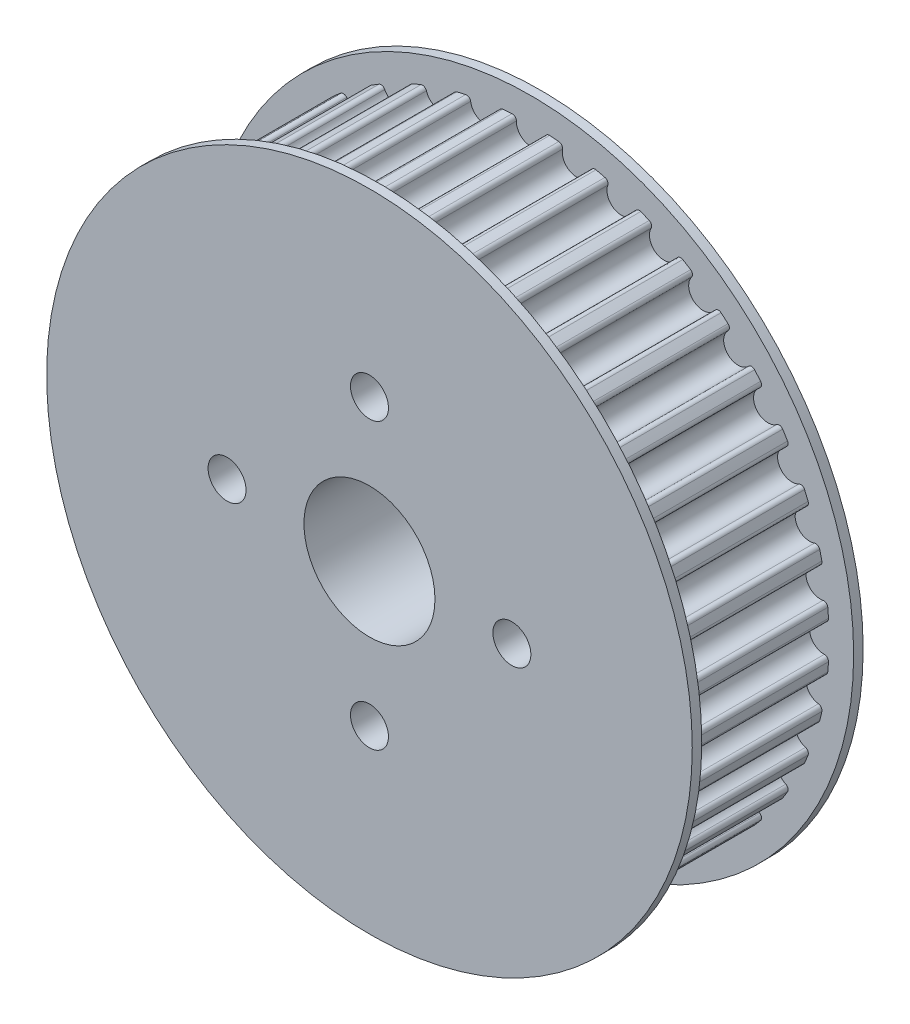
SolidWorks part; units mm, degrees
ref_plane "Front Plane" through (0, 0, 0) normal (0, 0, 1) x (1, 0, 0)
ref_plane "Top Plane" through (0, 0, 0) normal (0, 1, 0) x (1, 0, 0)
ref_plane "Right Plane" through (0, 0, 0) normal (1, 0, 0) x (0, 0, -1)
sketch "Sketch1" plane through (0, 0, 0) normal (0, 0, 1) x (1, 0, 0)
  line L0 (0, 0) -> (0, 52.0511) construction
  line L1 (0, 0) -> (78.6588, 0) construction
  line L2 (0, 0) -> (7.0914, 44.7731) construction
  arc A2 (0, 29.35) -> (1.5246, 30.9088) centre (0, 30.875) ccw
  arc A3 (1.9816, 31.3474) -> (1.5246, 30.9088) centre (1.9545, 30.9183) ccw
  arc A4 (3.3293, 30.7667) -> (4.5914, 28.9887) centre (4.8299, 30.4949) ccw
  arc A5 (3.3293, 30.7667) -> (2.9466, 31.2715) centre (2.9062, 30.8434) ccw
  arc A6 (2.9466, 31.2715) -> (1.9816, 31.3474) centre (0, 0) ccw
  arc A7 (4.5914, 28.9887) -> (6.3411, 30.2897) centre (4.8299, 30.4949) ccw
  arc A8 (6.8611, 30.6515) -> (6.3411, 30.2897) centre (6.7671, 30.2319) ccw
  arc A9 (7.8022, 30.4255) -> (6.8611, 30.6515) centre (0, 0) ccw
  arc A10 (8.1013, 29.8671) -> (7.8022, 30.4255) centre (7.6954, 30.009) ccw
  arc A11 (8.1013, 29.8671) -> (9.0696, 27.9135) centre (9.5409, 29.3639) ccw
  arc A12 (9.0696, 27.9135) -> (11.0013, 28.9248) centre (9.5409, 29.3639) ccw
  arc A13 (11.5715, 29.2008) -> (11.0013, 28.9248) centre (11.4131, 28.8011) ccw
  arc A14 (12.4658, 28.8304) -> (11.5715, 29.2008) centre (0, 0) ccw
  arc A15 (12.6738, 28.2321) -> (12.4658, 28.8304) centre (12.2951, 28.4357) ccw
  arc A16 (12.6738, 28.2321) -> (13.3246, 26.151) centre (14.017, 27.5098) ccw
  arc A17 (13.3246, 26.151) -> (15.3907, 26.8477) centre (14.017, 27.5098) ccw
  arc A18 (15.9971, 27.0311) -> (15.3907, 26.8477) centre (15.7781, 26.6611) ccw
  arc A19 (16.8224, 26.5254) -> (15.9971, 27.0311) centre (0, 0) ccw
  arc A20 (16.9343, 25.9019) -> (16.8224, 26.5254) centre (16.5921, 26.1623) ccw
  arc A21 (16.9343, 25.9019) -> (17.2515, 23.7446) centre (18.1479, 24.9784) ccw
  arc A22 (17.2515, 23.7446) -> (19.4012, 24.1096) centre (18.1479, 24.9784) ccw
  arc A23 (20.0287, 24.1958) -> (19.4012, 24.1096) centre (19.7546, 23.8646) ccw
  arc A24 (20.7647, 23.5672) -> (20.0287, 24.1958) centre (0, 0) ccw
  arc A25 (20.7777, 22.9339) -> (20.7647, 23.5672) centre (20.4805, 23.2446) ccw
  arc A26 (20.7777, 22.9339) -> (20.7536, 20.7536) centre (21.8319, 21.8319) ccw
  arc A27 (20.7536, 20.7536) -> (22.9339, 20.7777) centre (21.8319, 21.8319) ccw
  arc A28 (23.5672, 20.7647) -> (22.9339, 20.7777) centre (23.2446, 20.4805) ccw
  arc A29 (24.1958, 20.0287) -> (23.5672, 20.7647) centre (0, 0) ccw
  arc A30 (24.1096, 19.4012) -> (24.1958, 20.0287) centre (23.8646, 19.7546) ccw
  arc A31 (24.1096, 19.4012) -> (23.7446, 17.2515) centre (24.9784, 18.1479) ccw
  arc A32 (23.7446, 17.2515) -> (25.9019, 16.9343) centre (24.9784, 18.1479) ccw
  arc A33 (26.5254, 16.8224) -> (25.9019, 16.9343) centre (26.1623, 16.5921) ccw
  arc A34 (27.0311, 15.9971) -> (26.5254, 16.8224) centre (0, 0) ccw
  arc A35 (26.8477, 15.3907) -> (27.0311, 15.9971) centre (26.6611, 15.7781) ccw
  arc A36 (26.8477, 15.3907) -> (26.151, 13.3246) centre (27.5098, 14.017) ccw
  arc A37 (26.151, 13.3246) -> (28.2321, 12.6738) centre (27.5098, 14.017) ccw
  arc A38 (28.8304, 12.4658) -> (28.2321, 12.6738) centre (28.4357, 12.2951) ccw
  arc A39 (29.2008, 11.5715) -> (28.8304, 12.4658) centre (0, 0) ccw
  arc A40 (28.9248, 11.0013) -> (29.2008, 11.5715) centre (28.8011, 11.4131) ccw
  arc A41 (28.9248, 11.0013) -> (27.9135, 9.0696) centre (29.3639, 9.5409) ccw
  arc A42 (27.9135, 9.0696) -> (29.8671, 8.1013) centre (29.3639, 9.5409) ccw
  arc A43 (30.4255, 7.8022) -> (29.8671, 8.1013) centre (30.009, 7.6954) ccw
  arc A44 (30.6515, 6.8611) -> (30.4255, 7.8022) centre (0, 0) ccw
  arc A45 (30.2897, 6.3411) -> (30.6515, 6.8611) centre (30.2319, 6.7671) ccw
  arc A46 (30.2897, 6.3411) -> (28.9887, 4.5914) centre (30.4949, 4.8299) ccw
  arc A47 (28.9887, 4.5914) -> (30.7667, 3.3293) centre (30.4949, 4.8299) ccw
  arc A48 (31.2715, 2.9466) -> (30.7667, 3.3293) centre (30.8434, 2.9062) ccw
  arc A49 (31.3474, 1.9816) -> (31.2715, 2.9466) centre (0, 0) ccw
  arc A50 (30.9088, 1.5246) -> (31.3474, 1.9816) centre (30.9183, 1.9545) ccw
  arc A51 (30.9088, 1.5246) -> (29.35, 0) centre (30.875, 0) ccw
  arc A52 (29.35, 0) -> (30.9088, -1.5246) centre (30.875, 0) ccw
  arc A53 (31.3474, -1.9816) -> (30.9088, -1.5246) centre (30.9183, -1.9545) ccw
  arc A54 (31.2715, -2.9466) -> (31.3474, -1.9816) centre (0, 0) ccw
  arc A55 (30.7667, -3.3293) -> (31.2715, -2.9466) centre (30.8434, -2.9062) ccw
  arc A56 (30.7667, -3.3293) -> (28.9887, -4.5914) centre (30.4949, -4.8299) ccw
  arc A57 (28.9887, -4.5914) -> (30.2897, -6.3411) centre (30.4949, -4.8299) ccw
  arc A58 (30.6515, -6.8611) -> (30.2897, -6.3411) centre (30.2319, -6.7671) ccw
  arc A59 (30.4255, -7.8022) -> (30.6515, -6.8611) centre (0, 0) ccw
  arc A60 (29.8671, -8.1013) -> (30.4255, -7.8022) centre (30.009, -7.6954) ccw
  arc A61 (29.8671, -8.1013) -> (27.9135, -9.0696) centre (29.3639, -9.5409) ccw
  arc A62 (27.9135, -9.0696) -> (28.9248, -11.0013) centre (29.3639, -9.5409) ccw
  arc A63 (29.2008, -11.5715) -> (28.9248, -11.0013) centre (28.8011, -11.4131) ccw
  arc A64 (28.8304, -12.4658) -> (29.2008, -11.5715) centre (0, 0) ccw
  arc A65 (28.2321, -12.6738) -> (28.8304, -12.4658) centre (28.4357, -12.2951) ccw
  arc A66 (28.2321, -12.6738) -> (26.151, -13.3246) centre (27.5098, -14.017) ccw
  arc A67 (26.151, -13.3246) -> (26.8477, -15.3907) centre (27.5098, -14.017) ccw
  arc A68 (27.0311, -15.9971) -> (26.8477, -15.3907) centre (26.6611, -15.7781) ccw
  arc A69 (26.5254, -16.8224) -> (27.0311, -15.9971) centre (0, 0) ccw
  arc A70 (25.9019, -16.9343) -> (26.5254, -16.8224) centre (26.1623, -16.5921) ccw
  arc A71 (25.9019, -16.9343) -> (23.7446, -17.2515) centre (24.9784, -18.1479) ccw
  arc A72 (23.7446, -17.2515) -> (24.1096, -19.4012) centre (24.9784, -18.1479) ccw
  arc A73 (24.1958, -20.0287) -> (24.1096, -19.4012) centre (23.8646, -19.7546) ccw
  arc A74 (23.5672, -20.7647) -> (24.1958, -20.0287) centre (0, 0) ccw
  arc A75 (22.9339, -20.7777) -> (23.5672, -20.7647) centre (23.2446, -20.4805) ccw
  arc A76 (22.9339, -20.7777) -> (20.7536, -20.7536) centre (21.8319, -21.8319) ccw
  arc A77 (20.7536, -20.7536) -> (20.7777, -22.9339) centre (21.8319, -21.8319) ccw
  arc A78 (20.7647, -23.5672) -> (20.7777, -22.9339) centre (20.4805, -23.2446) ccw
  arc A79 (20.0287, -24.1958) -> (20.7647, -23.5672) centre (0, 0) ccw
  arc A80 (19.4012, -24.1096) -> (20.0287, -24.1958) centre (19.7546, -23.8646) ccw
  arc A81 (19.4012, -24.1096) -> (17.2515, -23.7446) centre (18.1479, -24.9784) ccw
  arc A82 (17.2515, -23.7446) -> (16.9343, -25.9019) centre (18.1479, -24.9784) ccw
  arc A83 (16.8224, -26.5254) -> (16.9343, -25.9019) centre (16.5921, -26.1623) ccw
  arc A84 (15.9971, -27.0311) -> (16.8224, -26.5254) centre (0, 0) ccw
  arc A85 (15.3907, -26.8477) -> (15.9971, -27.0311) centre (15.7781, -26.6611) ccw
  arc A86 (15.3907, -26.8477) -> (13.3246, -26.151) centre (14.017, -27.5098) ccw
  arc A87 (13.3246, -26.151) -> (12.6738, -28.2321) centre (14.017, -27.5098) ccw
  arc A88 (12.4658, -28.8304) -> (12.6738, -28.2321) centre (12.2951, -28.4357) ccw
  arc A89 (11.5715, -29.2008) -> (12.4658, -28.8304) centre (0, 0) ccw
  arc A90 (11.0013, -28.9248) -> (11.5715, -29.2008) centre (11.4131, -28.8011) ccw
  arc A91 (11.0013, -28.9248) -> (9.0696, -27.9135) centre (9.5409, -29.3639) ccw
  arc A92 (9.0696, -27.9135) -> (8.1013, -29.8671) centre (9.5409, -29.3639) ccw
  arc A93 (7.8022, -30.4255) -> (8.1013, -29.8671) centre (7.6954, -30.009) ccw
  arc A94 (6.8611, -30.6515) -> (7.8022, -30.4255) centre (0, 0) ccw
  arc A95 (6.3411, -30.2897) -> (6.8611, -30.6515) centre (6.7671, -30.2319) ccw
  arc A96 (6.3411, -30.2897) -> (4.5914, -28.9887) centre (4.8299, -30.4949) ccw
  arc A97 (4.5914, -28.9887) -> (3.3293, -30.7667) centre (4.8299, -30.4949) ccw
  arc A98 (2.9466, -31.2715) -> (3.3293, -30.7667) centre (2.9062, -30.8434) ccw
  arc A99 (1.9816, -31.3474) -> (2.9466, -31.2715) centre (0, 0) ccw
  arc A100 (1.5246, -30.9088) -> (1.9816, -31.3474) centre (1.9545, -30.9183) ccw
  arc A101 (1.5246, -30.9088) -> (0, -29.35) centre (0, -30.875) ccw
  arc A102 (0, -29.35) -> (-1.5246, -30.9088) centre (0, -30.875) ccw
  arc A103 (-1.9816, -31.3474) -> (-1.5246, -30.9088) centre (-1.9545, -30.9183) ccw
  arc A104 (-2.9466, -31.2715) -> (-1.9816, -31.3474) centre (0, 0) ccw
  arc A105 (-3.3293, -30.7667) -> (-2.9466, -31.2715) centre (-2.9062, -30.8434) ccw
  arc A106 (-3.3293, -30.7667) -> (-4.5914, -28.9887) centre (-4.8299, -30.4949) ccw
  arc A107 (-4.5914, -28.9887) -> (-6.3411, -30.2897) centre (-4.8299, -30.4949) ccw
  arc A108 (-6.8611, -30.6515) -> (-6.3411, -30.2897) centre (-6.7671, -30.2319) ccw
  arc A109 (-7.8022, -30.4255) -> (-6.8611, -30.6515) centre (0, 0) ccw
  arc A110 (-8.1013, -29.8671) -> (-7.8022, -30.4255) centre (-7.6954, -30.009) ccw
  arc A111 (-8.1013, -29.8671) -> (-9.0696, -27.9135) centre (-9.5409, -29.3639) ccw
  arc A112 (-9.0696, -27.9135) -> (-11.0013, -28.9248) centre (-9.5409, -29.3639) ccw
  arc A113 (-11.5715, -29.2008) -> (-11.0013, -28.9248) centre (-11.4131, -28.8011) ccw
  arc A114 (-12.4658, -28.8304) -> (-11.5715, -29.2008) centre (0, 0) ccw
  arc A115 (-12.6738, -28.2321) -> (-12.4658, -28.8304) centre (-12.2951, -28.4357) ccw
  arc A116 (-12.6738, -28.2321) -> (-13.3246, -26.151) centre (-14.017, -27.5098) ccw
  arc A117 (-13.3246, -26.151) -> (-15.3907, -26.8477) centre (-14.017, -27.5098) ccw
  arc A118 (-15.9971, -27.0311) -> (-15.3907, -26.8477) centre (-15.7781, -26.6611) ccw
  arc A119 (-16.8224, -26.5254) -> (-15.9971, -27.0311) centre (0, 0) ccw
  arc A120 (-16.9343, -25.9019) -> (-16.8224, -26.5254) centre (-16.5921, -26.1623) ccw
  arc A121 (-16.9343, -25.9019) -> (-17.2515, -23.7446) centre (-18.1479, -24.9784) ccw
  arc A122 (-17.2515, -23.7446) -> (-19.4012, -24.1096) centre (-18.1479, -24.9784) ccw
  arc A123 (-20.0287, -24.1958) -> (-19.4012, -24.1096) centre (-19.7546, -23.8646) ccw
  arc A124 (-20.7647, -23.5672) -> (-20.0287, -24.1958) centre (0, 0) ccw
  arc A125 (-20.7777, -22.9339) -> (-20.7647, -23.5672) centre (-20.4805, -23.2446) ccw
  arc A126 (-20.7777, -22.9339) -> (-20.7536, -20.7536) centre (-21.8319, -21.8319) ccw
  arc A127 (-20.7536, -20.7536) -> (-22.9339, -20.7777) centre (-21.8319, -21.8319) ccw
  arc A128 (-23.5672, -20.7647) -> (-22.9339, -20.7777) centre (-23.2446, -20.4805) ccw
  arc A129 (-24.1958, -20.0287) -> (-23.5672, -20.7647) centre (0, 0) ccw
  arc A130 (-24.1096, -19.4012) -> (-24.1958, -20.0287) centre (-23.8646, -19.7546) ccw
  arc A131 (-24.1096, -19.4012) -> (-23.7446, -17.2515) centre (-24.9784, -18.1479) ccw
  arc A132 (-23.7446, -17.2515) -> (-25.9019, -16.9343) centre (-24.9784, -18.1479) ccw
  arc A133 (-26.5254, -16.8224) -> (-25.9019, -16.9343) centre (-26.1623, -16.5921) ccw
  arc A134 (-27.0311, -15.9971) -> (-26.5254, -16.8224) centre (0, 0) ccw
  arc A135 (-26.8477, -15.3907) -> (-27.0311, -15.9971) centre (-26.6611, -15.7781) ccw
  arc A136 (-26.8477, -15.3907) -> (-26.151, -13.3246) centre (-27.5098, -14.017) ccw
  arc A137 (-26.151, -13.3246) -> (-28.2321, -12.6738) centre (-27.5098, -14.017) ccw
  arc A138 (-28.8304, -12.4658) -> (-28.2321, -12.6738) centre (-28.4357, -12.2951) ccw
  arc A139 (-29.2008, -11.5715) -> (-28.8304, -12.4658) centre (0, 0) ccw
  arc A140 (-28.9248, -11.0013) -> (-29.2008, -11.5715) centre (-28.8011, -11.4131) ccw
  arc A141 (-28.9248, -11.0013) -> (-27.9135, -9.0696) centre (-29.3639, -9.5409) ccw
  arc A142 (-27.9135, -9.0696) -> (-29.8671, -8.1013) centre (-29.3639, -9.5409) ccw
  arc A143 (-30.4255, -7.8022) -> (-29.8671, -8.1013) centre (-30.009, -7.6954) ccw
  arc A144 (-30.6515, -6.8611) -> (-30.4255, -7.8022) centre (0, 0) ccw
  arc A145 (-30.2897, -6.3411) -> (-30.6515, -6.8611) centre (-30.2319, -6.7671) ccw
  arc A146 (-30.2897, -6.3411) -> (-28.9887, -4.5914) centre (-30.4949, -4.8299) ccw
  arc A147 (-28.9887, -4.5914) -> (-30.7667, -3.3293) centre (-30.4949, -4.8299) ccw
  arc A148 (-31.2715, -2.9466) -> (-30.7667, -3.3293) centre (-30.8434, -2.9062) ccw
  arc A149 (-31.3474, -1.9816) -> (-31.2715, -2.9466) centre (0, 0) ccw
  arc A150 (-30.9088, -1.5246) -> (-31.3474, -1.9816) centre (-30.9183, -1.9545) ccw
  arc A151 (-30.9088, -1.5246) -> (-29.35, 0) centre (-30.875, 0) ccw
  arc A152 (-29.35, 0) -> (-30.9088, 1.5246) centre (-30.875, 0) ccw
  arc A153 (-31.3474, 1.9816) -> (-30.9088, 1.5246) centre (-30.9183, 1.9545) ccw
  arc A154 (-31.2715, 2.9466) -> (-31.3474, 1.9816) centre (0, 0) ccw
  arc A155 (-30.7667, 3.3293) -> (-31.2715, 2.9466) centre (-30.8434, 2.9062) ccw
  arc A156 (-30.7667, 3.3293) -> (-28.9887, 4.5914) centre (-30.4949, 4.8299) ccw
  arc A157 (-28.9887, 4.5914) -> (-30.2897, 6.3411) centre (-30.4949, 4.8299) ccw
  arc A158 (-30.6515, 6.8611) -> (-30.2897, 6.3411) centre (-30.2319, 6.7671) ccw
  arc A159 (-30.4255, 7.8022) -> (-30.6515, 6.8611) centre (0, 0) ccw
  arc A160 (-29.8671, 8.1013) -> (-30.4255, 7.8022) centre (-30.009, 7.6954) ccw
  arc A161 (-29.8671, 8.1013) -> (-27.9135, 9.0696) centre (-29.3639, 9.5409) ccw
  arc A162 (-27.9135, 9.0696) -> (-28.9248, 11.0013) centre (-29.3639, 9.5409) ccw
  arc A163 (-29.2008, 11.5715) -> (-28.9248, 11.0013) centre (-28.8011, 11.4131) ccw
  arc A164 (-28.8304, 12.4658) -> (-29.2008, 11.5715) centre (0, 0) ccw
  arc A165 (-28.2321, 12.6738) -> (-28.8304, 12.4658) centre (-28.4357, 12.2951) ccw
  arc A166 (-28.2321, 12.6738) -> (-26.151, 13.3246) centre (-27.5098, 14.017) ccw
  arc A167 (-26.151, 13.3246) -> (-26.8477, 15.3907) centre (-27.5098, 14.017) ccw
  arc A168 (-27.0311, 15.9971) -> (-26.8477, 15.3907) centre (-26.6611, 15.7781) ccw
  arc A169 (-26.5254, 16.8224) -> (-27.0311, 15.9971) centre (0, 0) ccw
  arc A170 (-25.9019, 16.9343) -> (-26.5254, 16.8224) centre (-26.1623, 16.5921) ccw
  arc A171 (-25.9019, 16.9343) -> (-23.7446, 17.2515) centre (-24.9784, 18.1479) ccw
  arc A172 (-23.7446, 17.2515) -> (-24.1096, 19.4012) centre (-24.9784, 18.1479) ccw
  arc A173 (-24.1958, 20.0287) -> (-24.1096, 19.4012) centre (-23.8646, 19.7546) ccw
  arc A174 (-23.5672, 20.7647) -> (-24.1958, 20.0287) centre (0, 0) ccw
  arc A175 (-22.9339, 20.7777) -> (-23.5672, 20.7647) centre (-23.2446, 20.4805) ccw
  arc A176 (-22.9339, 20.7777) -> (-20.7536, 20.7536) centre (-21.8319, 21.8319) ccw
  arc A177 (-20.7536, 20.7536) -> (-20.7777, 22.9339) centre (-21.8319, 21.8319) ccw
  arc A178 (-20.7647, 23.5672) -> (-20.7777, 22.9339) centre (-20.4805, 23.2446) ccw
  arc A179 (-20.0287, 24.1958) -> (-20.7647, 23.5672) centre (0, 0) ccw
  arc A180 (-19.4012, 24.1096) -> (-20.0287, 24.1958) centre (-19.7546, 23.8646) ccw
  arc A181 (-19.4012, 24.1096) -> (-17.2515, 23.7446) centre (-18.1479, 24.9784) ccw
  arc A182 (-17.2515, 23.7446) -> (-16.9343, 25.9019) centre (-18.1479, 24.9784) ccw
  arc A183 (-16.8224, 26.5254) -> (-16.9343, 25.9019) centre (-16.5921, 26.1623) ccw
  arc A184 (-15.9971, 27.0311) -> (-16.8224, 26.5254) centre (0, 0) ccw
  arc A185 (-15.3907, 26.8477) -> (-15.9971, 27.0311) centre (-15.7781, 26.6611) ccw
  arc A186 (-15.3907, 26.8477) -> (-13.3246, 26.151) centre (-14.017, 27.5098) ccw
  arc A187 (-13.3246, 26.151) -> (-12.6738, 28.2321) centre (-14.017, 27.5098) ccw
  arc A188 (-12.4658, 28.8304) -> (-12.6738, 28.2321) centre (-12.2951, 28.4357) ccw
  arc A189 (-11.5715, 29.2008) -> (-12.4658, 28.8304) centre (0, 0) ccw
  arc A190 (-11.0013, 28.9248) -> (-11.5715, 29.2008) centre (-11.4131, 28.8011) ccw
  arc A191 (-11.0013, 28.9248) -> (-9.0696, 27.9135) centre (-9.5409, 29.3639) ccw
  arc A192 (-9.0696, 27.9135) -> (-8.1013, 29.8671) centre (-9.5409, 29.3639) ccw
  arc A193 (-7.8022, 30.4255) -> (-8.1013, 29.8671) centre (-7.6954, 30.009) ccw
  arc A194 (-6.8611, 30.6515) -> (-7.8022, 30.4255) centre (0, 0) ccw
  arc A195 (-6.3411, 30.2897) -> (-6.8611, 30.6515) centre (-6.7671, 30.2319) ccw
  arc A196 (-6.3411, 30.2897) -> (-4.5914, 28.9887) centre (-4.8299, 30.4949) ccw
  arc A197 (-4.5914, 28.9887) -> (-3.3293, 30.7667) centre (-4.8299, 30.4949) ccw
  arc A198 (-2.9466, 31.2715) -> (-3.3293, 30.7667) centre (-2.9062, 30.8434) ccw
  arc A199 (-1.9816, 31.3474) -> (-2.9466, 31.2715) centre (0, 0) ccw
  arc A200 (-1.5246, 30.9088) -> (-1.9816, 31.3474) centre (-1.9545, 30.9183) ccw
  arc A201 (-1.5246, 30.9088) -> (0, 29.35) centre (0, 30.875) ccw
  point P409 (0, 0)
  dimension "D1" = 40
  dimension "D3" = 3.05
  dimension "D4" = 0.86
  dimension "D6" = 3.05
  dimension "D7" = 0.86
extrude "Boss-Extrude1" add sketch "Sketch1" along normal blind 16
sketch "Sketch2" plane through (0, 0, 16) normal (0, 0, 1) x (1, 0, 0)
  circle A0 centre (0, 0) radius 34
  dimension "D1" = 68
extrude "Boss-Extrude2" add sketch "Sketch2" along normal blind 1
ref_plane "Plane1" through (0, 0, 8) normal (0, 0, -1) x (-1, 0, 0)
mirror "Mirror1" about plane through (0, 0, 8) normal (0, 0, -1) of "Boss-Extrude2"
sketch "Sketch3" plane through (0, 0, 17) normal (0, 0, 1) x (1, 0, 0)
  circle A0 centre (0, 0) radius 6.9
  circle A1 centre (15, 0) radius 2
  circle A2 centre (0, -15) radius 2
  circle A3 centre (-15, 0) radius 2
  circle A4 centre (0, 15) radius 2
  point P14 (0, 0)
  dimension "D1" = 13.8
  dimension "D3" = 4
  dimension "D2" = 15
  dimension "D4" = 4
extrude "Cut-Extrude1" cut sketch "Sketch3" against normal through all
sketch "Sketch4" plane through (0, 0, 17) normal (0, 0, 1) x (1, 0, 0)
  line L0 (-15, 0) -> (15, 0) construction
  line L1 (0, 15) -> (0, -15) construction
